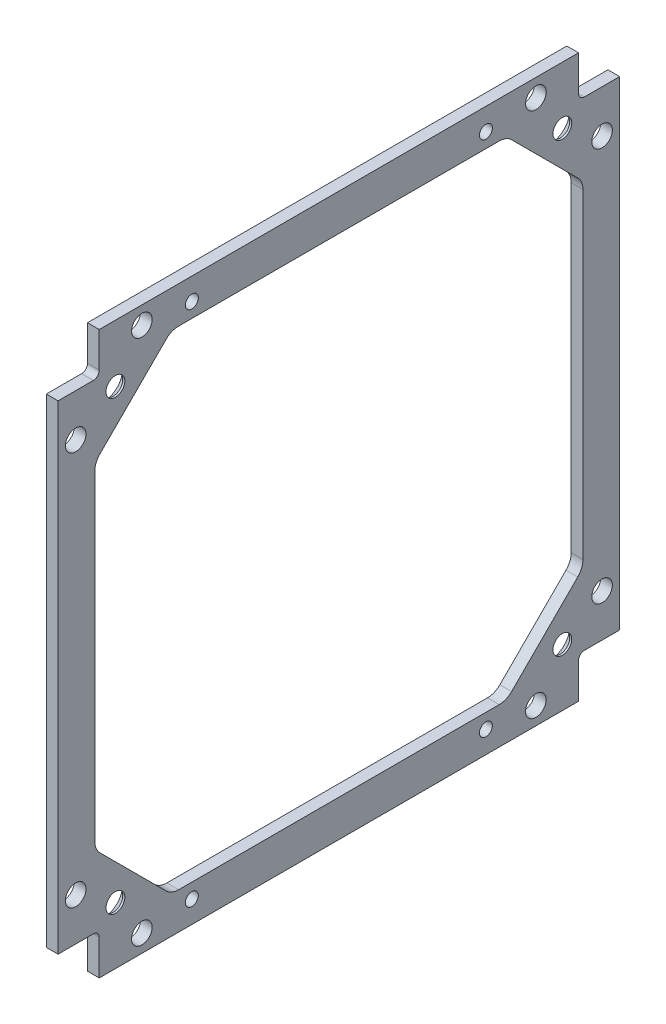
SolidWorks part; units mm, degrees
ref_plane "Front Plane" through (0, 0, 0) normal (0, 0, 1) x (1, 0, 0)
ref_plane "Top Plane" through (0, 0, 0) normal (0, 1, 0) x (1, 0, 0)
ref_plane "Right Plane" through (0, 0, 0) normal (1, 0, 0) x (0, 0, -1)
sketch "Sketch2" plane through (-51.4936, 0, 0) normal (-1, 0, 0) x (0, 0, 1)
  line L0 (0.4347, 3.9519) -> (7.4347, 3.9519)
  line L1 (7.4347, 3.9519) -> (7.4347, 85.4519)
  line L2 (0.4347, 92.4519) -> (-81.0653, 92.4519)
  line L3 (-88.0653, 85.4519) -> (-88.0653, 3.9519)
  line L4 (-81.0653, -3.0481) -> (0.4347, -3.0481)
  line L5 (0.4347, -3.0481) -> (0.4347, 3.9519)
  line L6 (-81.0653, -3.0481) -> (-81.0653, 3.9519)
  line L7 (-81.0653, 3.9519) -> (-88.0653, 3.9519)
  line L8 (-40.3153, 92.4519) -> (-40.3153, -3.0481) construction
  line L9 (-81.8153, 73.2019) -> (-81.8153, 16.2019)
  line L10 (7.4347, 44.7019) -> (-88.0653, 44.7019) construction
  line L11 (-88.0653, 85.4519) -> (-81.0653, 85.4519)
  line L12 (-81.0653, 92.4519) -> (-81.0653, 85.4519)
  line L13 (-68.8153, 3.2019) -> (-11.8153, 3.2019)
  line L14 (-81.8153, 73.2019) -> (-68.8153, 86.2019)
  line L15 (7.4347, 85.4519) -> (0.4347, 85.4519)
  line L16 (0.4347, 92.4519) -> (0.4347, 85.4519)
  line L17 (1.1847, 16.2019) -> (1.1847, 73.2019)
  line L18 (-11.8153, 86.2019) -> (1.1847, 73.2019)
  line L19 (-11.8153, 86.2019) -> (-68.8153, 86.2019)
  line L28 (-11.8153, 3.2019) -> (1.1847, 16.2019)
  line L29 (-81.8153, 16.2019) -> (-68.8153, 3.2019)
  dimension "D1" = 95.5
  dimension "D2" = 95.5
  dimension "D3" = 41.5
  dimension "D4" = 41.5
  dimension "D5" = 41.5
  dimension "D6" = 41.5
  dimension "D7" = 7
  dimension "D8" = 28.5
  dimension "D9" = 28.5
  dimension "D10" = 28.5
  dimension "D11" = 28.5
  dimension "D12" = 28.5
extrude "Boss-Extrude2" add sketch "Sketch2" along normal blind 2
hole_wizard "Ø3.5 (3.5) Diameter Hole1" positions "Sketch19" profile "Sketch18" hole size "Ø3.5" standard "Ansi Metric" end condition up to next
sketch "Sketch19" plane through (-53.4936, 0, 0) normal (-1, 0, 0) x (0, 0, 1)
  line L1 (-81.0653, -3.0481) -> (0.4347, -3.0481) construction
  line L2 (-88.0653, 85.4519) -> (-88.0653, 3.9519) construction
  line L7 (7.4347, 3.9519) -> (7.4347, 85.4519) construction
  line L10 (0.4347, 92.4519) -> (-81.0653, 92.4519) construction
  line L13 (-88.0653, 44.7019) -> (7.4347, 44.7019) construction
  line L15 (-40.3153, 92.4519) -> (-40.3153, -3.0481) construction
  point P0 (-73.8153, -0.0481)
  point P6 (-85.0653, 11.2019)
  point P8 (-85.0653, 78.2019)
  point P10 (-73.8153, 89.4519)
  point P12 (-6.8153, 89.4519)
  point P14 (4.4347, 78.2019)
  point P16 (4.4347, 11.2019)
  point P18 (-6.8153, -0.0481)
  dimension "D1" = 33.5
  dimension "D2" = 44.75
  dimension "D3" = 33.5
  dimension "D4" = 44.75
  dimension "D5" = 33.5
  dimension "D6" = 44.75
  dimension "D7" = 33.5
  dimension "D8" = 44.75
sketch "Sketch18" plane through (-53.4936, -0.0481, -73.8153) normal (0, 1, 0) x (0, 0, 1)
  line L0 (0, 0) -> (0, 2)
  line L1 (0, 2) -> (1.75, 2)
  line L2 (1.75, 2) -> (1.75, 0)
  line L5 (1.75, 0) -> (0, 0)
  line L11 (0, -6.35) -> (0, 107.95) construction
  dimension "Thru Hole Dia." = 3.5
  dimension "Thru Hole Depth" = 2
hole_wizard "CSK for M3 Flat Countersunk Head Screw5" positions "3DSketch2" profile "Sketch24" countersink size "M3" standard "JIS" end condition up to next
sketch3d "3DSketch2"
  line L8 (-53.4936, 44.7019, -88.0653) -> (-53.4936, 44.7019, 7.4347) construction
  line L9 (-53.4936, 85.4519, -88.0653) -> (-53.4936, 3.9519, -88.0653) construction
  line L10 (-53.4936, 3.9519, 7.4347) -> (-53.4936, 85.4519, 7.4347) construction
  line L12 (-53.4936, 92.4519, -40.3153) -> (-53.4936, -3.0481, -40.3153) construction
  line L13 (-53.4936, 92.4519, 0.4347) -> (-53.4936, 92.4519, -81.0653) construction
  line L14 (-53.4936, -3.0481, -81.0653) -> (-53.4936, -3.0481, 0.4347) construction
  point P0 (-53.4936, 6.7019, -78.3153)
  point P2 (-53.4936, 82.7019, -78.3153)
  point P4 (-53.4936, 82.7019, -2.3153)
  point P19 (-53.4936, 6.7019, -2.3153)
  dimension "D1" = 38
  dimension "D2" = 38
  dimension "D3" = 38
  dimension "D4" = 38
  dimension "D5" = 38
  dimension "D6" = 38
  dimension "D7" = 38
  dimension "D8" = 38
sketch "Sketch24" plane through (-53.4936, 6.7019, -78.3153) normal (0, 1, 0) x (0, 0, 1)
  line L0 (0, 0) -> (0, 2)
  line L1 (0, 2) -> (1.6, 2)
  line L2 (1.6, 2) -> (1.6, 1.65)
  line L3 (1.6, 1.65) -> (3.25, 0)
  line L5 (3.25, 0) -> (0, 0)
  line L6 (-1.6, 1.65) -> (-3.25, 0) construction
  line L11 (0, -6.35) -> (0, 107.95) construction
  dimension "Thru Hole Dia." = 3.2
  dimension "Thru Hole Depth" = 2
  dimension "Near C'Sink Dia." = 6.5
  dimension "Near C'Sink Angle" = 90
hole_wizard "Ø2.2 (2.2) Diameter Hole1" positions "3DSketch3" profile "Sketch25" hole size "Ø2.2" standard "Ansi Metric" end condition up to next
sketch3d "3DSketch3"
  line L0 (-53.4936, 92.4519, 0.4347) -> (-53.4936, 92.4519, -81.0653) construction
  line L3 (-53.4936, 3.9519, 7.4347) -> (-53.4936, 85.4519, 7.4347) construction
  line L4 (-53.4936, -3.0481, -81.0653) -> (-53.4936, -3.0481, 0.4347) construction
  line L6 (-53.4936, 85.4519, -88.0653) -> (-53.4936, 3.9519, -88.0653) construction
  line L7 (-53.4936, 44.7019, -88.0653) -> (-53.4936, 44.7019, 7.4347) construction
  line L9 (-53.4936, 92.4519, -40.3153) -> (-53.4936, -3.0481, -40.3153) construction
  point P0 (-53.4936, 88.7019, -65.3153)
  point P2 (-53.4936, 88.7019, -15.3153)
  point P4 (-53.4936, 0.7019, -65.3153)
  point P6 (-53.4936, 0.7019, -15.3153)
  dimension "D1" = 25
  dimension "D2" = 44
  dimension "D3" = 25
  dimension "D4" = 44
  dimension "D5" = 25
  dimension "D6" = 44
  dimension "D7" = 25
  dimension "D8" = 44
sketch "Sketch25" plane through (-53.4936, 88.7019, -65.3153) normal (0, 1, 0) x (0, 0, 1)
  line L0 (0, 0) -> (0, 2)
  line L1 (0, 2) -> (1.1, 2)
  line L2 (1.1, 2) -> (1.1, 0)
  line L5 (1.1, 0) -> (0, 0)
  line L11 (0, -6.35) -> (0, 107.95) construction
  dimension "Thru Hole Dia." = 2.2
  dimension "Thru Hole Depth" = 2
fillet "Fillet1" radius 3 8 edges at (-52.4936, 16.2019, 1.1847) (-52.4936, 3.2019, -11.8153) (-52.4936, 3.2019, -68.8153) (-52.4936, 16.2019, -81.8153) (-52.4936, 73.2019, 1.1847) (-52.4936, 86.2019, -11.8153) (-52.4936, 73.2019, -81.8153) (-52.4936, 86.2019, -68.8153)
fillet "Fillet2" radius 1 4 edges at (-52.4936, 3.9519, -81.0653) (-52.4936, 3.9519, 0.4347) (-52.4936, 85.4519, 0.4347) (-52.4936, 85.4519, -81.0653)
